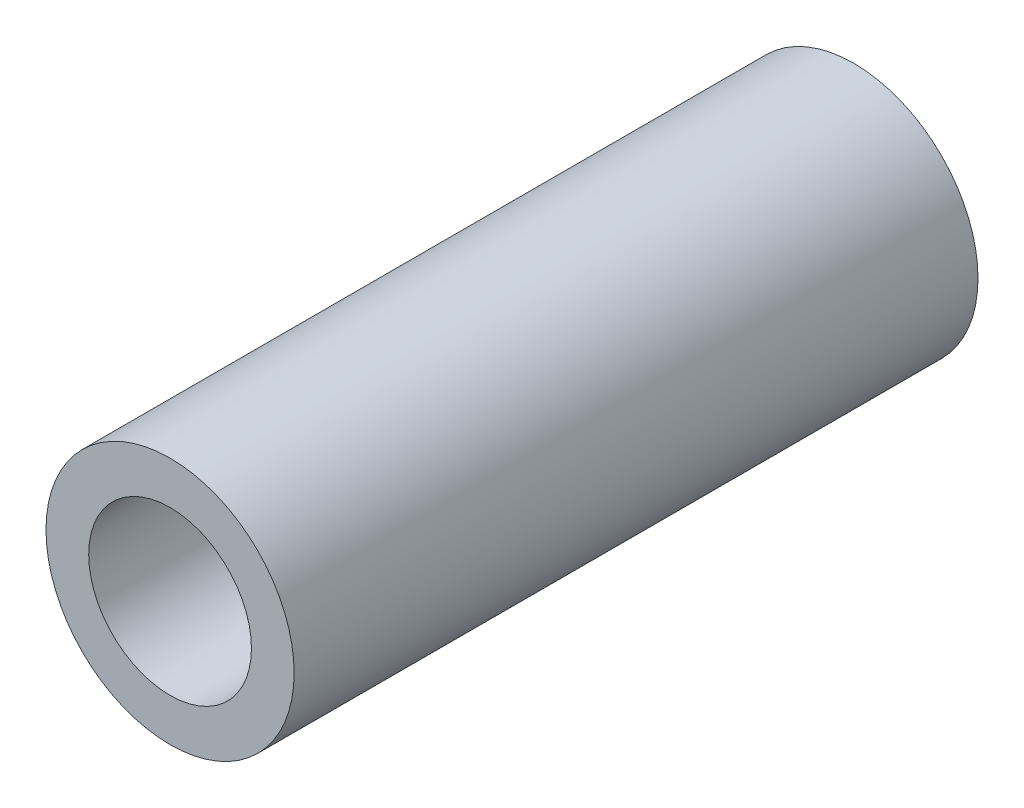
SolidWorks part; units mm, degrees
ref_plane "Front" through (0, 0, 0) normal (0, 0, 1) x (1, 0, 0)
ref_plane "Top" through (0, 0, 0) normal (0, 1, 0) x (1, 0, 0)
ref_plane "Right" through (0, 0, 0) normal (1, 0, 0) x (0, 0, -1)
sketch "Sketch1" plane through (0, 0, 0) normal (0, 0, 1) x (1, 0, 0)
  circle A0 centre (0, 0) radius 6.35
  circle A1 centre (0, 0) radius 4.165
  dimension "D1" = 12.7
  dimension "D2" = 8.33
extrude "Boss-Extrude1" add sketch "Sketch1" along normal blind 35
